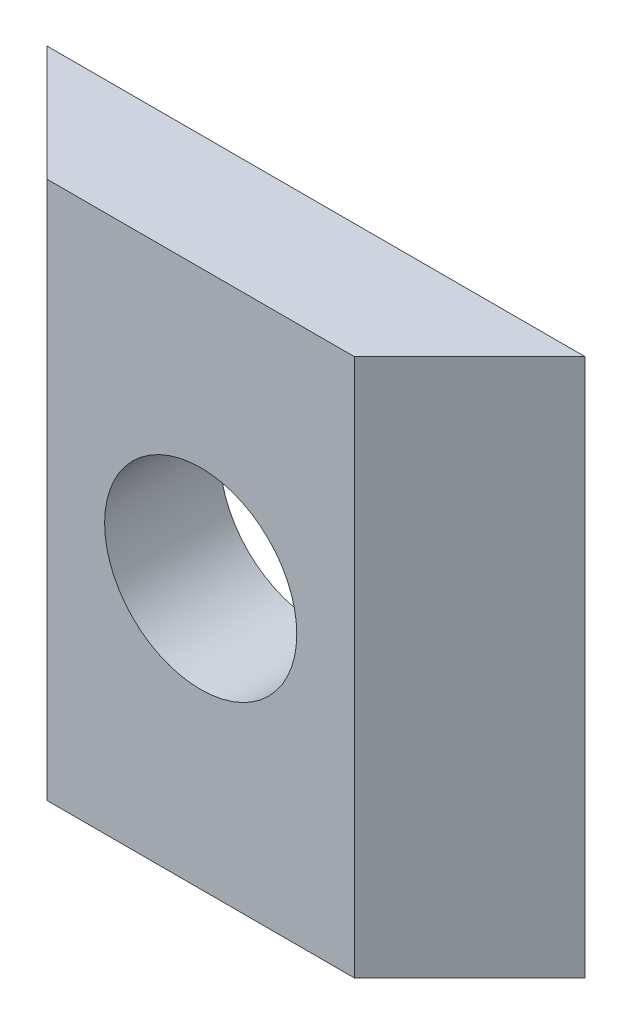
SolidWorks part; units mm, degrees
material "Cast Stainless Steel"
ref_plane "Plano frontal" through (0, 0, 0) normal (0, 0, 1) x (1, 0, 0)
ref_plane "Plano superior" through (0, 0, 0) normal (0, 1, 0) x (1, 0, 0)
ref_plane "Plano direito" through (0, 0, 0) normal (1, 0, 0) x (0, 0, -1)
sketch "Sketch1" plane through (0, 0, 0) normal (0, 1, 0) x (1, 0, 0)
  line L0 (-7, 1.5) -> (-4, -1.5)
  line L1 (-7, 1.5) -> (7, 1.5)
  line L2 (-7, 1.5) -> (-7, -1.5)
  line L3 (-7, -1.5) -> (7, -1.5)
  line L4 (7, 1.5) -> (7, -1.5)
  line L5 (-7, 1.5) -> (7, -1.5) construction
  line L6 (-7, -1.5) -> (7, 1.5) construction
  line L7 (7, 1.5) -> (4, -1.5)
  point P0 (0, 0)
  dimension "D1" = 14
  dimension "D2" = 3
  dimension "D3" = 135
  dimension "D4" = 135
extrude "Boss-Extrude1" add sketch "Sketch1" along normal mid plane 14 contours L7 L1 L0 L3
sketch "Sketch2" plane through (0, 0, -1.5) normal (0, 0, -1) x (-1, 0, 0)
  circle A0 centre (0, 0) radius 2.5
  dimension "D1" = 5
extrude "Cut-Extrude1" cut sketch "Sketch2" against normal blind 14
